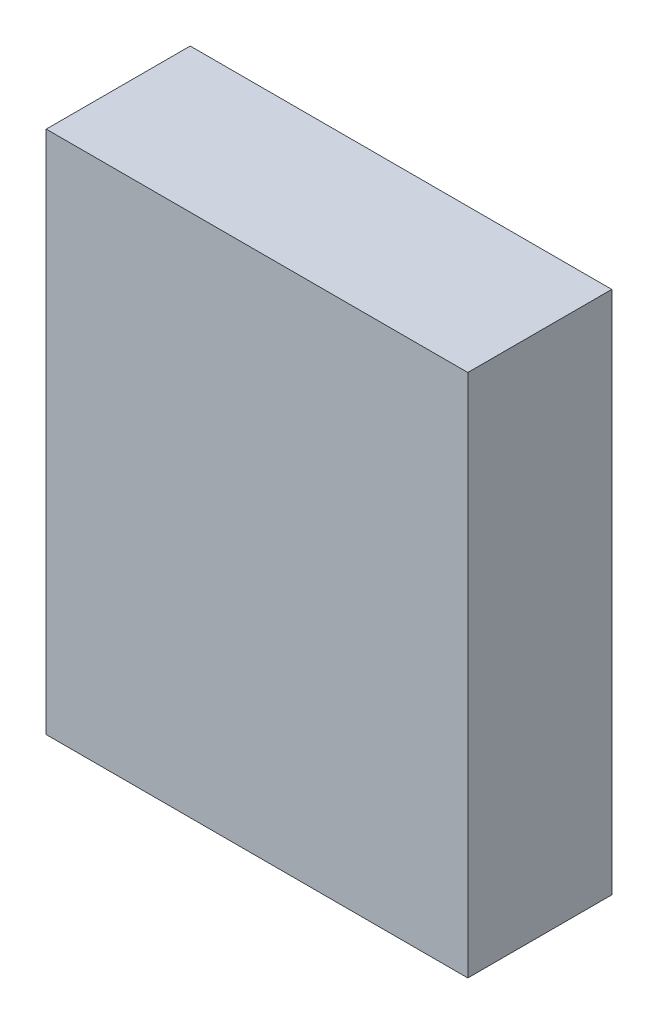
SolidWorks part; units mm, degrees
material "PPU Custom"
ref_plane "Front Plane" through (0, 0, 0) normal (0, 0, 1) x (1, 0, 0)
ref_plane "Top Plane" through (0, 0, 0) normal (0, 1, 0) x (1, 0, 0)
ref_plane "Right Plane" through (0, 0, 0) normal (1, 0, 0) x (0, 0, -1)
sketch "Sketch1" plane through (0, 0, 0) normal (0, 0, 1) x (1, 0, 0)
  line L2 (-205, -255) -> (205, -255)
  line L3 (-205, -255) -> (-205, 255)
  line L4 (-205, 255) -> (205, 255)
  line L5 (205, -255) -> (205, 255)
  line L6 (-205, -255) -> (205, 255) construction
  line L7 (-205, 255) -> (205, -255) construction
  point P2 (0, 0)
  dimension "D1" = 410
  dimension "D2" = 510
extrude "Boss-Extrude1" add sketch "Sketch1" along normal blind 140
